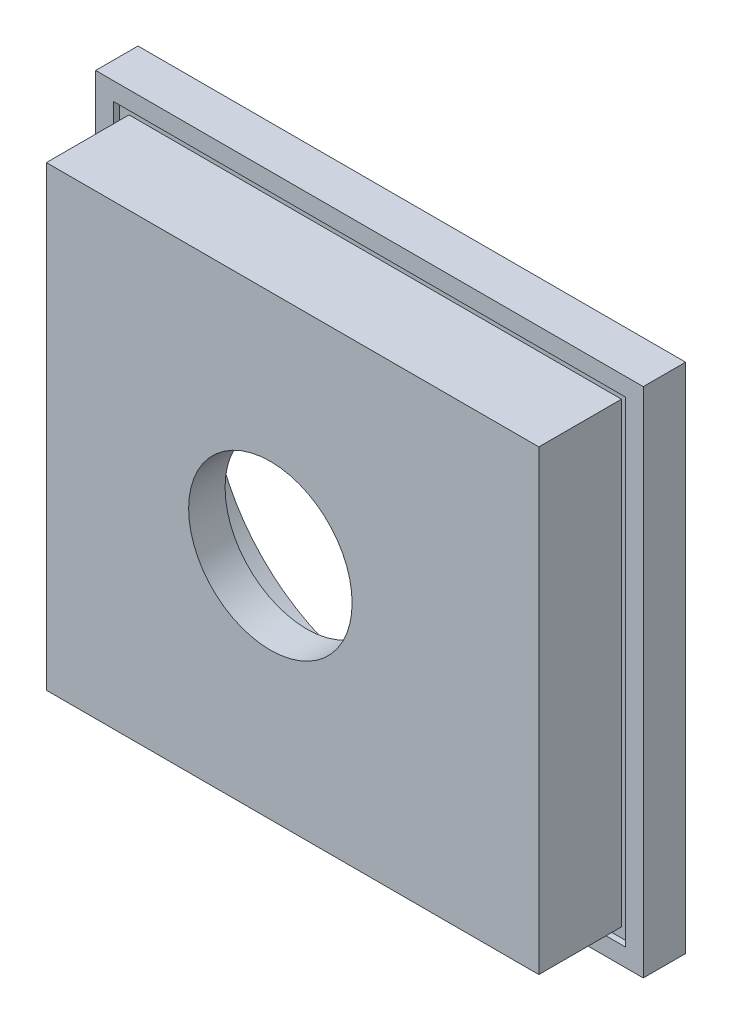
SolidWorks part; units mm, degrees
ref_plane "Front Plane" through (0, 0, 0) normal (0, 0, 1) x (1, 0, 0)
ref_plane "Top Plane" through (0, 0, 0) normal (0, 1, 0) x (1, 0, 0)
ref_plane "Right Plane" through (0, 0, 0) normal (1, 0, 0) x (0, 0, -1)
sketch "Sketch1" plane through (0, 0, 0) normal (0, 0, 1) x (1, 0, 0)
  line L1 (0, 0) -> (278, 0)
  line L2 (0, 0) -> (0, 260)
  line L3 (0, 260) -> (278, 260)
  line L4 (278, 0) -> (278, 260)
  dimension "D1" = 278
  dimension "D2" = 260
extrude "Boss-Extrude1" add sketch "Sketch1" along normal blind 60.5
sketch "Sketch2" plane through (0, 0, 0) normal (0, 0, 1) x (1, 0, 0)
  line L0 (0, 260) -> (0, 0) construction
  line L5 (278, 260) -> (0, 260) construction
  circle A0 centre (127.7, 130) radius 90.5
  point P5 (0, 130)
  point P9 (139, 260)
  dimension "D1" = 181
  dimension "D2" = 11.3
extrude "Cut-Extrude2" cut sketch "Sketch2" along normal blind 42
sketch "Sketch3" plane through (0, 0, 0) normal (0, 0, 1) x (1, 0, 0)
  circle A0 centre (127.7, 130) radius 41.5
  circle A1 centre (127.7, 130) radius 90.5 construction
  dimension "D1" = 83
extrude "Cut-Extrude3" cut sketch "Sketch3" along normal through all
sketch "Sketch4" plane through (0, 0, 0) normal (0, 0, 1) x (1, 0, 0)
  circle A0 centre (127.7, 130) radius 99.95
  circle A1 centre (127.7, 130) radius 95.05
  dimension "D1" = 190.1
  dimension "D2" = 199.9
extrude "Cut-Extrude5" cut sketch "Sketch4" along normal blind 2.95
sketch "Sketch5" plane through (0, 0, 0) normal (0, 0, 1) x (1, 0, 0)
  line L0 (127.7, 22.5) -> (127.7, 237.5) construction
  line L1 (127.7, 130) -> (181.45, 223.0977) construction
  line L2 (127.7, 130) -> (73.95, 223.0977) construction
  line L3 (127.7, 130) -> (73.95, 36.9023) construction
  line L4 (127.7, 130) -> (181.45, 36.9023) construction
  circle A0 centre (127.7, 130) radius 107.5 construction
  point P4 (73.95, 223.0977)
  point P5 (20.2, 130)
  point P6 (181.45, 36.9023)
  point P7 (73.95, 36.9023)
  point P8 (235.2, 130)
  point P14 (181.45, 223.0977)
  dimension "D1" = 215
  dimension "D2" = 30
  dimension "D3" = 30
  dimension "D4" = 30
  dimension "D5" = 30
ref_plane "Plane1" through (0, 0, 60.5) normal (0, 0, 1) x (1, 0, 0)
sketch "Sketch6" plane through (0, 0, 60.5) normal (0, 0, 1) x (1, 0, 0)
  line L1 (0, 260) -> (278, 260)
  line L2 (0, 260) -> (0, 0)
  line L3 (0, 0) -> (278, 0)
  line L4 (278, 260) -> (278, 0)
  line L5 (14, 246) -> (264, 246)
  line L6 (14, 246) -> (14, 14)
  line L7 (14, 14) -> (264, 14)
  line L8 (264, 246) -> (264, 14)
  point P10 (139, 246)
  point P11 (139, 260)
  point P12 (264, 130)
  point P13 (278, 130)
  dimension "D1" = 14
  dimension "D2" = 14
extrude "Cut-Extrude6" cut sketch "Sketch6" against normal blind 39
sketch "Sketch7" plane through (0, 0, 60.5) normal (0, 0, 1) x (1, 0, 0)
  line L1 (14, 14) -> (264, 14)
  line L2 (14, 14) -> (14, 246)
  line L3 (14, 246) -> (264, 246)
  line L4 (264, 14) -> (264, 246)
  line L5 (9.1, 250.9) -> (268.9, 250.9)
  line L6 (9.1, 250.9) -> (9.1, 9.1)
  line L7 (9.1, 9.1) -> (268.9, 9.1)
  line L8 (268.9, 250.9) -> (268.9, 9.1)
  dimension "D1" = 4.9
  dimension "D2" = 4.9
  dimension "D3" = 4.9
  dimension "D4" = 4.9
extrude "Cut-Extrude7" cut sketch "Sketch7" against normal blind 41.95
hole_wizard "Ø8.0mm Dowel Hole1" positions "Sketch8" profile "Sketch9" hole size "Ø8.0" standard "ISO"
sketch "Sketch8" plane through (0, 0, 0) normal (0, 0, -1) x (-1, 0, 0)
  circle A0 centre (-127.7, 130) radius 107.5 construction
  point P0 (-181.45, 223.0977)
  point P6 (-77.931, 225.2854)
  point P10 (-20.2, 130)
  point P13 (-73.95, 36.9023)
  point P16 (-181.45, 36.9023)
  point P19 (-235.2, 130)
  point P23 (0, 0)
sketch "Sketch9" plane through (181.45, 223.0977, 0) normal (1, 0, 0) x (0, 1, 0)
  line L0 (0, 0) -> (0, 17.4034)
  line L1 (0, 17.4034) -> (4, 15)
  line L2 (4, 15) -> (4, 0)
  line L5 (4, 0) -> (0, 0)
  line L10 (0, 17.4034) -> (-4, 15) construction
  line L11 (0, -6.35) -> (0, 107.95) construction
  dimension "Hole Dia." = 8
  dimension "Hole Depth" = 15
  dimension "Drill Angle" = 118
sketch "Sketch10" plane through (0, 0, 0) normal (0, 1, 0) x (1, 0, 0)
  line L0 (0, 0) -> (278, 0) construction
  circle A0 centre (127.7, -9) radius 3
  point P4 (0, 0)
  dimension "D1" = 6
  dimension "D2" = 9
extrude "Cut-Extrude8" cut sketch "Sketch10" along normal blind 59
